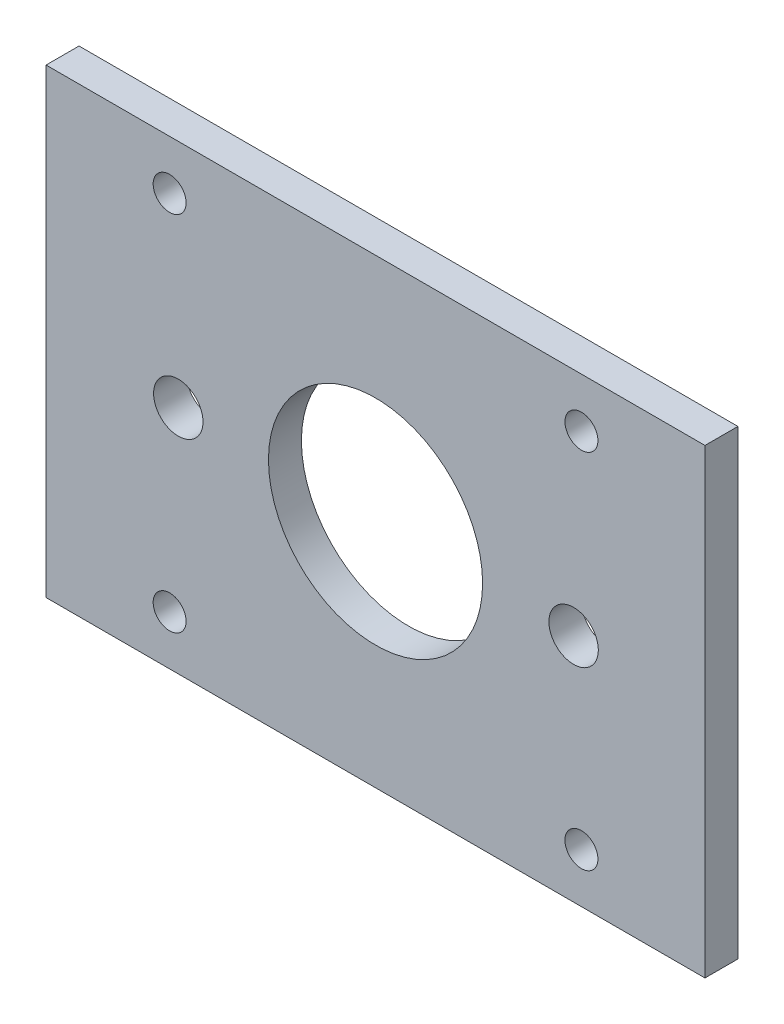
SolidWorks part; units mm, degrees
ref_plane "Front" through (0, 0, 0) normal (0, 0, 1) x (1, 0, 0)
ref_plane "Top" through (0, 0, 0) normal (0, 1, 0) x (1, 0, 0)
ref_plane "Right" through (0, 0, 0) normal (1, 0, 0) x (0, 0, -1)
sketch "草图1" plane through (0, 0, 0) normal (0, 0, 1) x (1, 0, 0)
  line L0 (-40, -35) -> (-40, 35) construction
  line L1 (40, -21) -> (-40, -21)
  line L2 (40, -21) -> (40, 35)
  line L3 (40, 35) -> (-40, 35)
  line L4 (-40, -21) -> (-40, 35)
  line L5 (40, -21) -> (-40, 35) construction
  line L6 (40, 35) -> (-40, -21) construction
  circle A0 centre (0, 7) radius 13
  circle A1 centre (0, 7) radius 13 construction
  point P0 (0, 7)
  dimension "D1" = 80
extrude "凸台-拉伸1" add sketch "草图1" along normal blind 4
sketch "草图2" plane through (0, 0, 4) normal (0, 0, 1) x (1, 0, 0)
  line L0 (-40, -35) -> (-40, 35) construction
  line L1 (-40, -21) -> (40, -21) construction
  circle A0 centre (-25, -15) radius 2
  dimension "D1" = 4
  dimension "D2" = 15
  dimension "D3" = 6
extrude "切除-拉伸1" cut sketch "草图2" against normal blind 100
pattern_linear "阵列(线性)1" count 2 spacing 44 along (0, 1, 0) count 2 spacing 50 along (1, 0, 0) of "切除-拉伸1"
sketch "草图3" plane through (0, 0, 4) normal (0, 0, 1) x (1, 0, 0)
  circle A0 centre (24.0511, 7) radius 3 construction
  circle A1 centre (-23.9489, 7) radius 3 construction
  circle A2 centre (24.0511, 7) radius 3
  circle A3 centre (-23.9489, 7) radius 3
extrude "切除-拉伸2" cut sketch "草图3" against normal blind 50
